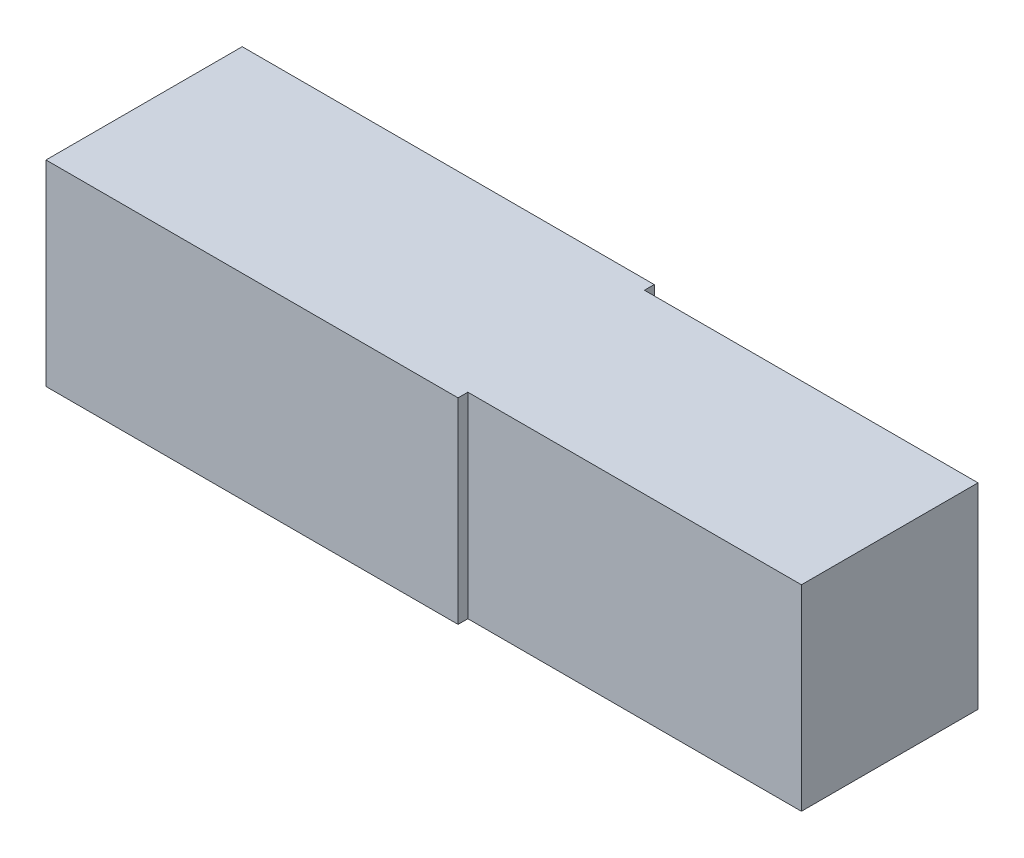
SolidWorks part; units mm, degrees
ref_plane "前视基准面" through (0, 0, 0) normal (0, 0, 1) x (1, 0, 0)
ref_plane "上视基准面" through (0, 0, 0) normal (0, 1, 0) x (1, 0, 0)
ref_plane "右视基准面" through (0, 0, 0) normal (1, 0, 0) x (0, 0, -1)
other "Configuration Table"
sketch "草图1" plane through (0, 0, 0) normal (0, 1, 0) x (1, 0, 0)
  line L5 (-10.5, -5) -> (10.5, -5)
  line L6 (-10.5, -5) -> (-10.5, 5)
  line L19 (-10.5, 5) -> (10.5, 5)
  line L20 (10.5, -5) -> (10.5, 5)
  line L29 (-10.5, -5) -> (10.5, 5) construction
  line L30 (-10.5, 5) -> (10.5, -5) construction
  line L31 (10.5, 4.5) -> (27.5, 4.5)
  line L32 (10.5, 4.5) -> (10.5, -4.5)
  line L33 (10.5, -4.5) -> (27.5, -4.5)
  line L34 (27.5, 4.5) -> (27.5, -4.5)
  point P0 (0, 0)
  dimension "D1" = 21
  dimension "D2" = 10
  dimension "D5" = 0.5
  dimension "D3" = 38
  dimension "D4" = 0.5
extrude "凸台-拉伸1" add sketch "草图1" along normal blind 10 contours L5 L20 L19 L6 | L31 L34 L33 L32
